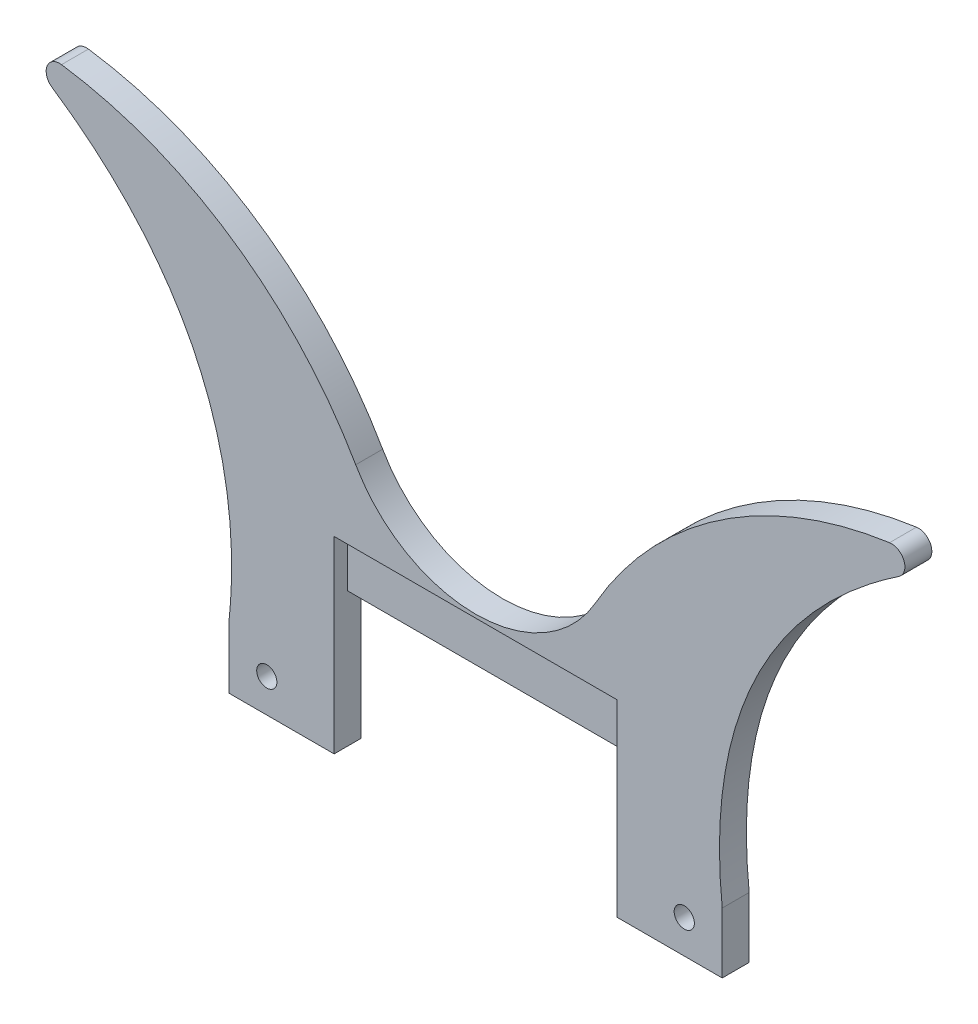
SolidWorks part; units mm, degrees
ref_plane "前视基准面" through (0, 0, 0) normal (0, 0, 1) x (1, 0, 0)
ref_plane "上视基准面" through (0, 0, 0) normal (0, 1, 0) x (1, 0, 0)
ref_plane "右视基准面" through (0, 0, 0) normal (1, 0, 0) x (0, 0, -1)
sketch "草图1" plane through (0, 0, 0) normal (0, 0, 1) x (1, 0, 0)
  line L0 (0, 0) -> (0, -62.1358) construction
  line L1 (36.6359, -39.9745) -> (-36.6359, -39.9745)
  arc A0 (-17.7938, -10.1798) -> (17.7938, -10.1798) centre (0, 0) ccw
  arc A1 (61.4836, 19.436) -> (17.7938, -10.1798) centre (69.8734, -39.9745) ccw
  arc A2 (-61.4836, 19.436) -> (-17.7938, -10.1798) centre (-69.8734, -39.9745) cw
  arc A3 (-62.879, 15.7958) -> (-61.4836, 19.436) centre (-61.7632, 17.4557) cw
  arc A4 (62.879, 15.7958) -> (61.4836, 19.436) centre (61.7632, 17.4557) ccw
  spline S0 degree 3 poles (-36.6359, -39.9745) (-34.1215, -16.7044) (-43.1396, 2.5277) (-62.879, 15.7958) knots 0 0 0 0 0.899908 0.899908 0.899908 0.899908
  spline S1 degree 3 poles (36.6359, -39.9745) (34.1215, -16.7044) (43.1396, 2.5277) (62.879, 15.7958) knots 0 0 0 0 0.899908 0.899908 0.899908 0.899908
  dimension "D1" = 41
  dimension "D2" = 120
  dimension "D3" = 2
extrude "凸台-拉伸1" add sketch "草图1" along normal blind 3
sketch "草图2" plane through (0, 0, 0) normal (0, 0, -1) x (-1, 0, 0)
  line L0 (36.6359, -39.9745) -> (-36.6359, -39.9745) construction
  line L1 (-21, -29) -> (21, -29)
  line L2 (-21, -29) -> (-21, -39.9745)
  line L3 (-21, -39.9745) -> (21, -39.9745)
  line L4 (21, -29) -> (21, -39.9745)
  arc A0 (-17.7938, -10.1798) -> (17.7938, -10.1798) centre (0, 0) ccw construction
  dimension "D3" = 29
  dimension "D1" = 42
  dimension "D2" = 21
extrude "切除-拉伸1" cut sketch "草图2" against normal blind 3
sketch "草图3" plane through (0, 0, 0) normal (0, 0, -1) x (-1, 0, 0)
  line L0 (0, -20.5) -> (0, -54.0456) construction
  line L1 (-36.6359, -39.9745) -> (-21, -39.9745)
  line L2 (-36.6359, -39.9745) -> (-36.6359, -48.9745)
  line L3 (-36.6359, -48.9745) -> (-21, -48.9745)
  line L4 (-21, -39.9745) -> (-21, -48.9745)
  line L5 (21, -29) -> (-21, -29) construction
  line L6 (21, -39.9745) -> (21, -48.9745)
  line L7 (36.6359, -48.9745) -> (21, -48.9745)
  line L8 (36.6359, -39.9745) -> (36.6359, -48.9745)
  line L9 (36.6359, -39.9745) -> (21, -39.9745)
  arc A0 (-17.7938, -10.1798) -> (17.7938, -10.1798) centre (0, 0) ccw construction
  circle A1 centre (-31, -44) radius 1.5
  circle A2 centre (31, -44) radius 1.5
  dimension "D4" = 3
  dimension "D1" = 10
  dimension "D2" = 15
  dimension "D3" = 9
extrude "凸台-拉伸2" add sketch "草图3" against normal blind 3
sketch "草图4" plane through (0, 0, 3) normal (0, 0, 1) x (1, 0, 0)
  line L2 (-21, -29) -> (-21, -21)
  line L3 (-21, -21) -> (21, -21)
  line L4 (21, -29) -> (21, -21)
  line L7 (-21, -29) -> (21, -29)
  line L8 (21, -29) -> (21, -48.9745)
  line L9 (21, -48.9745) -> (36.6359, -48.9745)
  line L10 (36.6359, -48.9745) -> (36.6359, -39.9745)
  line L11 (-36.6359, -39.9745) -> (-36.6359, -48.9745)
  line L12 (-36.6359, -48.9745) -> (-21, -48.9745)
  line L13 (-21, -48.9745) -> (-21, -29)
  line L15 (21, -29) -> (21, -48.9745)
  line L16 (21, -48.9745) -> (36.6359, -48.9745)
  line L17 (36.6359, -48.9745) -> (36.6359, -39.9745)
  line L18 (-36.6359, -39.9745) -> (-36.6359, -48.9745)
  line L19 (-36.6359, -48.9745) -> (-21, -48.9745)
  line L20 (-21, -48.9745) -> (-21, -29)
  arc A5 (62.879, 15.7958) -> (61.4836, 19.436) centre (61.7632, 17.4557) ccw
  arc A6 (61.4836, 19.436) -> (17.7938, -10.1798) centre (69.8734, -39.9745) ccw
  arc A7 (-17.7938, -10.1798) -> (17.7938, -10.1798) centre (0, 0) ccw
  arc A8 (-17.7938, -10.1798) -> (-61.4836, 19.436) centre (-69.8734, -39.9745) ccw
  arc A9 (-61.4836, 19.436) -> (-62.879, 15.7958) centre (-61.7632, 17.4557) ccw
  arc A10 (62.879, 15.7958) -> (61.4836, 19.436) centre (61.7632, 17.4557) ccw
  arc A11 (61.4836, 19.436) -> (17.7938, -10.1798) centre (69.8734, -39.9745) ccw
  arc A12 (-17.7938, -10.1798) -> (17.7938, -10.1798) centre (0, 0) ccw
  arc A13 (-17.7938, -10.1798) -> (-61.4836, 19.436) centre (-69.8734, -39.9745) ccw
  arc A14 (-61.4836, 19.436) -> (-62.879, 15.7958) centre (-61.7632, 17.4557) ccw
  spline S2 degree 3 poles (2945.8472, -352.8362) (-1424.5334, -1093.8575) (-204.4908, 1821.4988) (2262.3345, -1920.2954) knots -7.468535 -7.468535 -7.468535 -7.468535 8.275726 8.275726 8.275726 8.275726 only from (36.6359, -39.9745) to (62.879, 15.7958)
  spline S3 degree 3 poles (-2262.3233, -1920.2785) (204.4864, 1821.4778) (1424.5188, -1093.8374) (-2945.8043, -352.8435) knots -7.375794 -7.375794 -7.375794 -7.375794 8.368392 8.368392 8.368392 8.368392 only from (-62.879, 15.7958) to (-36.6359, -39.9745)
  spline S4 degree 3 poles (36.6359, -39.9745) (34.1215, -16.7044) (43.1396, 2.5277) (62.879, 15.7958) knots 0 0 0 0 0.899908 0.899908 0.899908 0.899908
  spline S5 degree 3 poles (-62.879, 15.7958) (-43.1396, 2.5277) (-34.1215, -16.7044) (-36.6359, -39.9745) knots 0 0 0 0 0.899908 0.899908 0.899908 0.899908
  dimension "D2" = 8
  dimension "D1" = 0
extrude "凸台-拉伸7" add sketch "草图4" along normal blind 1
sketch "草图5" plane through (0, 0, 3) normal (0, 0, 1) x (1, 0, 0)
  line L4 (-21, -21) -> (-21, -29)
  line L5 (-21, -29) -> (21, -29)
  line L6 (21, -29) -> (21, -21)
  line L7 (21, -21) -> (-21, -21)
  line L8 (-21, -21) -> (-21, -29)
  line L9 (-21, -29) -> (21, -29)
  line L10 (21, -29) -> (21, -21)
  line L11 (21, -21) -> (-21, -21)
  dimension "D1" = 0
extrude "切除-拉伸2" cut sketch "草图5" against normal blind 1
sketch "草图6" plane through (0, 0, 3) normal (0, 0, -1) x (-1, 0, 0)
  circle A0 centre (31, -44) radius 1.5 construction
  circle A1 centre (-31, -44) radius 1.5
  circle A2 centre (-31, -44) radius 1.5
  circle A3 centre (31, -44) radius 1.5
  dimension "D1" = 0
extrude "切除-拉伸3" cut sketch "草图6" against normal blind 1
